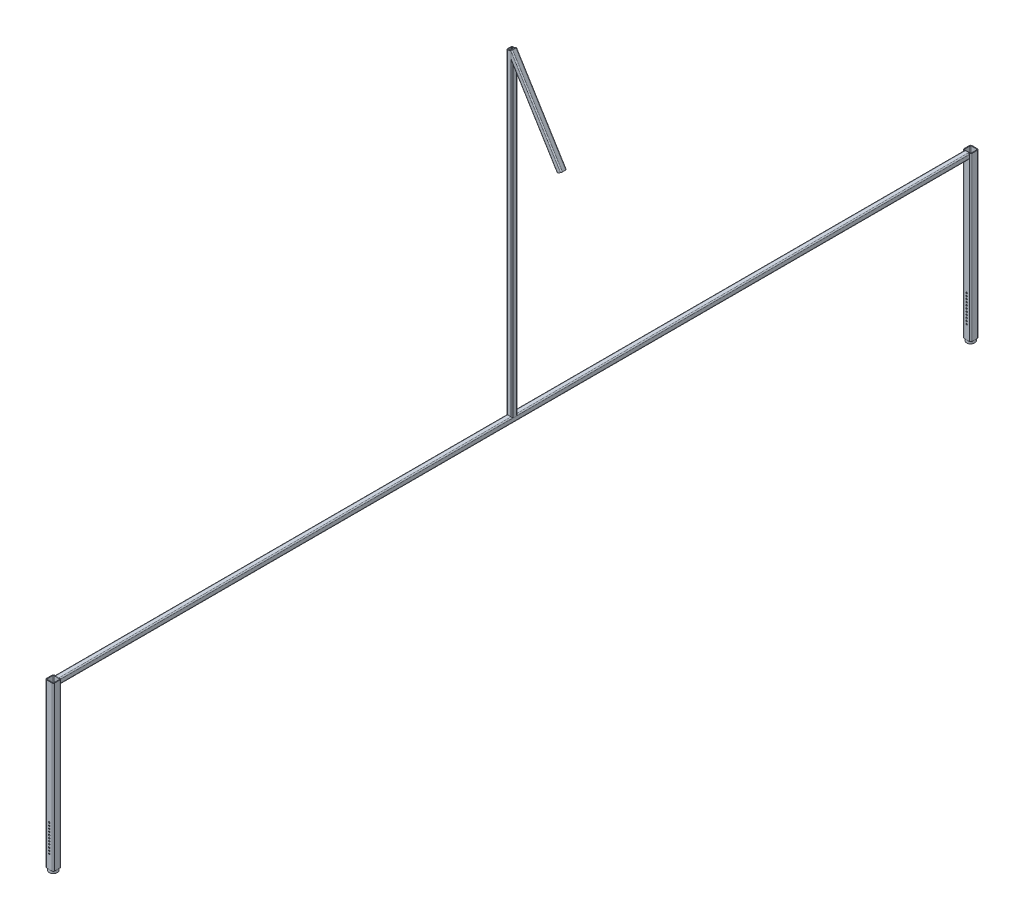
SolidWorks part; units mm, degrees
material "ASTM A36 Steel"
ref_plane "Front Plane" through (0, 0, 0) normal (0, 0, 1) x (1, 0, 0)
ref_plane "Top Plane" through (0, 0, 0) normal (0, 1, 0) x (1, 0, 0)
ref_plane "Right Plane" through (0, 0, 0) normal (1, 0, 0) x (0, 0, -1)
sketch "Sketch2" plane through (0, 0, 0) normal (0, 1, 0) x (1, 0, 0)
  line L2 (375.75, -1856.4583) -> (375.75, 1493.5417)
  point P0 (430.75, -181.4583)
  point P1 (0, 0)
other "Square tube 20 X 20 X 2(52)"
ref_plane "Plane22" through (375.75, 0, 1856.4583) normal (0, 0, -1) x (-1, 0, 0)
sketch "Sketch1" plane through (375.75, 0, 1856.4583) normal (0, 0, -1) x (-1, 0, 0)
  line L0 (-6, -8) -> (6, -8)
  line L1 (-8, -6) -> (-8, 6)
  line L2 (6, 8) -> (-6, 8)
  line L3 (8, 6) -> (8, -6)
  line L4 (-6, -10) -> (6, -10)
  line L5 (-10, -6) -> (-10, 6)
  line L6 (6, 10) -> (-6, 10)
  line L7 (10, 6) -> (10, -6)
  arc A0 (10, 6) -> (6, 10) centre (6, 6) ccw
  arc A1 (6, -10) -> (10, -6) centre (6, -6) ccw
  arc A2 (-10, -6) -> (-6, -10) centre (-6, -6) ccw
  arc A3 (-6, 10) -> (-10, 6) centre (-6, 6) ccw
  arc A4 (-6, 8) -> (-8, 6) centre (-6, 6) ccw
  arc A5 (8, 6) -> (6, 8) centre (6, 6) ccw
  arc A6 (6, -8) -> (8, -6) centre (6, -6) ccw
  arc A7 (-8, -6) -> (-6, -8) centre (-6, -6) ccw
  point P0 (-10, 0)
  point P1 (10, 0)
  point P2 (0, 10)
  point P3 (0, -10)
  point P4 (0, 0)
  point P5 (-10, -10)
  point P6 (10, -10)
  point P7 (10, 10)
  point P8 (-10, 10)
  point P33 (0, 0)
  dimension "D1" = 4
  dimension "Thickness" = 2
  dimension "V_leg" = 20
ref_plane "Plane23" through (0, 0, 1871.4583) normal (0, 0, 1) x (1, 0, 0)
sketch "Sketch145" plane through (0, 0, 1871.4583) normal (0, 0, 1) x (1, 0, 0)
  line L0 (375.7698, 10) -> (375.7698, -590)
  line L1 (369.75, 10) -> (381.75, 10) construction
  dimension "D1" = 600
other "Square tube 30 X 30 X 2.6(40)"
ref_plane "Plane24" through (375.7698, 10, 1871.4583) normal (0, -1, 0) x (1, 0, 0)
sketch "Sketch147" plane through (375.7698, 10, 1871.4583) normal (0, -1, 0) x (1, 0, 0)
  line L0 (-9.8, -12.4) -> (9.8, -12.4)
  line L1 (-12.4, -9.8) -> (-12.4, 9.8)
  line L2 (9.8, 12.4) -> (-9.8, 12.4)
  line L3 (12.4, 9.8) -> (12.4, -9.8)
  line L4 (-9.8, -15) -> (9.8, -15)
  line L5 (-15, -9.8) -> (-15, 9.8)
  line L6 (9.8, 15) -> (-9.8, 15)
  line L7 (15, 9.8) -> (15, -9.8)
  arc A0 (15, 9.8) -> (9.8, 15) centre (9.8, 9.8) ccw
  arc A1 (9.8, -15) -> (15, -9.8) centre (9.8, -9.8) ccw
  arc A2 (-15, -9.8) -> (-9.8, -15) centre (-9.8, -9.8) ccw
  arc A3 (-9.8, 15) -> (-15, 9.8) centre (-9.8, 9.8) ccw
  arc A4 (-9.8, 12.4) -> (-12.4, 9.8) centre (-9.8, 9.8) ccw
  arc A5 (12.4, 9.8) -> (9.8, 12.4) centre (9.8, 9.8) ccw
  arc A6 (9.8, -12.4) -> (12.4, -9.8) centre (9.8, -9.8) ccw
  arc A7 (-12.4, -9.8) -> (-9.8, -12.4) centre (-9.8, -9.8) ccw
  point P0 (-15, 0)
  point P1 (15, 0)
  point P2 (0, 15)
  point P3 (0, -15)
  point P4 (0, 0)
  point P5 (-15, -15)
  point P6 (15, -15)
  point P7 (15, 15)
  point P8 (-15, 15)
  point P33 (0, 0)
  dimension "D1" = 5.2
  dimension "Thickness" = 2.6
  dimension "V_leg" = 30
ref_plane "Plane25" through (0, 0, -1508.5417) normal (0, 0, -1) x (-1, 0, 0)
sketch "Sketch149" plane through (0, 0, -1508.5417) normal (0, 0, -1) x (-1, 0, 0)
  line L0 (-375.7698, 10) -> (-375.7698, -590)
  line L1 (-375.7698, 10) -> (-375.7698, -590) construction
  dimension "D1" = 600
other "Square tube 30 X 30 X 2.6(41)"
ref_plane "Plane26" through (375.7698, 10, -1508.5417) normal (0, -1, 0) x (-1, 0, 0)
sketch "Sketch148" plane through (375.7698, 10, -1508.5417) normal (0, -1, 0) x (-1, 0, 0)
  line L0 (-9.8, -12.4) -> (9.8, -12.4)
  line L1 (-12.4, -9.8) -> (-12.4, 9.8)
  line L2 (9.8, 12.4) -> (-9.8, 12.4)
  line L3 (12.4, 9.8) -> (12.4, -9.8)
  line L4 (-9.8, -15) -> (9.8, -15)
  line L5 (-15, -9.8) -> (-15, 9.8)
  line L6 (9.8, 15) -> (-9.8, 15)
  line L7 (15, 9.8) -> (15, -9.8)
  arc A0 (15, 9.8) -> (9.8, 15) centre (9.8, 9.8) ccw
  arc A1 (9.8, -15) -> (15, -9.8) centre (9.8, -9.8) ccw
  arc A2 (-15, -9.8) -> (-9.8, -15) centre (-9.8, -9.8) ccw
  arc A3 (-9.8, 15) -> (-15, 9.8) centre (-9.8, 9.8) ccw
  arc A4 (-9.8, 12.4) -> (-12.4, 9.8) centre (-9.8, 9.8) ccw
  arc A5 (12.4, 9.8) -> (9.8, 12.4) centre (9.8, 9.8) ccw
  arc A6 (9.8, -12.4) -> (12.4, -9.8) centre (9.8, -9.8) ccw
  arc A7 (-12.4, -9.8) -> (-9.8, -12.4) centre (-9.8, -9.8) ccw
  point P0 (-15, 0)
  point P1 (15, 0)
  point P2 (0, 15)
  point P3 (0, -15)
  point P4 (0, 0)
  point P5 (-15, -15)
  point P6 (15, -15)
  point P7 (15, 15)
  point P8 (-15, 15)
  point P33 (0, 0)
  dimension "D1" = 5.2
  dimension "Thickness" = 2.6
  dimension "V_leg" = 30
sketch "Sketch150" plane through (0, 0, -1523.5417) normal (0, 0, -1) x (-1, 0, 0)
  line L0 (-365.9698, -590) -> (-385.5698, -590) construction
  circle A0 centre (-375.7698, -540) radius 2.5
  dimension "D1" = 50
extrude "Cut-Extrude1" cut sketch "Sketch150" against normal through all both and the other way through all
pattern_linear "LPattern1" count 11 spacing 10 along (0, 1, 0) of "Cut-Extrude1"
ref_plane "Plane28" through (375.75, 0, 0) normal (1, 0, 0) x (0, 0, -1)
sketch "Sketch152" plane through (375.75, 0, 0) normal (1, 0, 0) x (0, 0, -1)
  line L0 (-181.4583, 0) -> (-181.4583, 1175)
  dimension "D1" = 1175
other "Square tube 20 X 20 X 2(65)"
ref_plane "Plane29" through (375.75, 0, 181.4583) normal (0, 1, 0) x (0, 0, 1)
sketch "Sketch151" plane through (375.75, 0, 181.4583) normal (0, 1, 0) x (0, 0, 1)
  line L0 (-6, -8) -> (6, -8)
  line L1 (-8, -6) -> (-8, 6)
  line L2 (6, 8) -> (-6, 8)
  line L3 (8, 6) -> (8, -6)
  line L4 (-6, -10) -> (6, -10)
  line L5 (-10, -6) -> (-10, 6)
  line L6 (6, 10) -> (-6, 10)
  line L7 (10, 6) -> (10, -6)
  arc A0 (10, 6) -> (6, 10) centre (6, 6) ccw
  arc A1 (6, -10) -> (10, -6) centre (6, -6) ccw
  arc A2 (-10, -6) -> (-6, -10) centre (-6, -6) ccw
  arc A3 (-6, 10) -> (-10, 6) centre (-6, 6) ccw
  arc A4 (-6, 8) -> (-8, 6) centre (-6, 6) ccw
  arc A5 (8, 6) -> (6, 8) centre (6, 6) ccw
  arc A6 (6, -8) -> (8, -6) centre (6, -6) ccw
  arc A7 (-8, -6) -> (-6, -8) centre (-6, -6) ccw
  point P0 (-10, 0)
  point P1 (10, 0)
  point P2 (0, 10)
  point P3 (0, -10)
  point P4 (0, 0)
  point P5 (-10, -10)
  point P6 (10, -10)
  point P7 (10, 10)
  point P8 (-10, 10)
  point P33 (0, 0)
  dimension "D1" = 4
  dimension "Thickness" = 2
  dimension "V_leg" = 20
ref_plane "Plane30" through (0, 0, 181.4583) normal (0, 0, 1) x (1, 0, 0)
sketch "Sketch153" plane through (0, 0, 181.4583) normal (0, 0, 1) x (1, 0, 0)
  line L0 (375.75, 1175) -> (559.3531, 877.0237)
  line L1 (375.75, 0) -> (375.75, 1175) construction
  dimension "D1" = 350
  dimension "D2" = 31.64
other "Square tube 20 X 20 X 2(66)"
ref_plane "Plane31" through (375.75, 1175, 181.4583) normal (0.5246, -0.8514, 0) x (0.8514, 0.5246, 0)
sketch "Sketch154" plane through (375.75, 1175, 181.4583) normal (0.5246, -0.8514, 0) x (0.8514, 0.5246, 0)
  line L0 (-6, -8) -> (6, -8)
  line L1 (-8, -6) -> (-8, 6)
  line L2 (6, 8) -> (-6, 8)
  line L3 (8, 6) -> (8, -6)
  line L4 (-6, -10) -> (6, -10)
  line L5 (-10, -6) -> (-10, 6)
  line L6 (6, 10) -> (-6, 10)
  line L7 (10, 6) -> (10, -6)
  arc A0 (10, 6) -> (6, 10) centre (6, 6) ccw
  arc A1 (6, -10) -> (10, -6) centre (6, -6) ccw
  arc A2 (-10, -6) -> (-6, -10) centre (-6, -6) ccw
  arc A3 (-6, 10) -> (-10, 6) centre (-6, 6) ccw
  arc A4 (-6, 8) -> (-8, 6) centre (-6, 6) ccw
  arc A5 (8, 6) -> (6, 8) centre (6, 6) ccw
  arc A6 (6, -8) -> (8, -6) centre (6, -6) ccw
  arc A7 (-8, -6) -> (-6, -8) centre (-6, -6) ccw
  point P0 (-10, 0)
  point P1 (10, 0)
  point P2 (0, 10)
  point P3 (0, -10)
  point P4 (0, 0)
  point P5 (-10, -10)
  point P6 (10, -10)
  point P7 (10, 10)
  point P8 (-10, 10)
  point P33 (0, 0)
  dimension "D1" = 4
  dimension "Thickness" = 2
  dimension "V_leg" = 20
sketch "Sketch155" plane through (0, -590, 0) normal (0, -1, 0) x (1, 0, 0)
  circle A0 centre (375.7698, 1871.4583) radius 12.4
  circle A1 centre (375.7698, 1871.4583) radius 15
extrude "Boss-Extrude1" add sketch "Sketch155" along normal blind 10 separate body
sketch "Sketch156" plane through (0, -590, 0) normal (0, -1, 0) x (1, 0, 0)
  circle A0 centre (375.7698, -1508.5417) radius 12.4
  circle A1 centre (375.7698, -1508.5417) radius 15
extrude "Boss-Extrude2" add sketch "Sketch156" along normal blind 10 separate body
